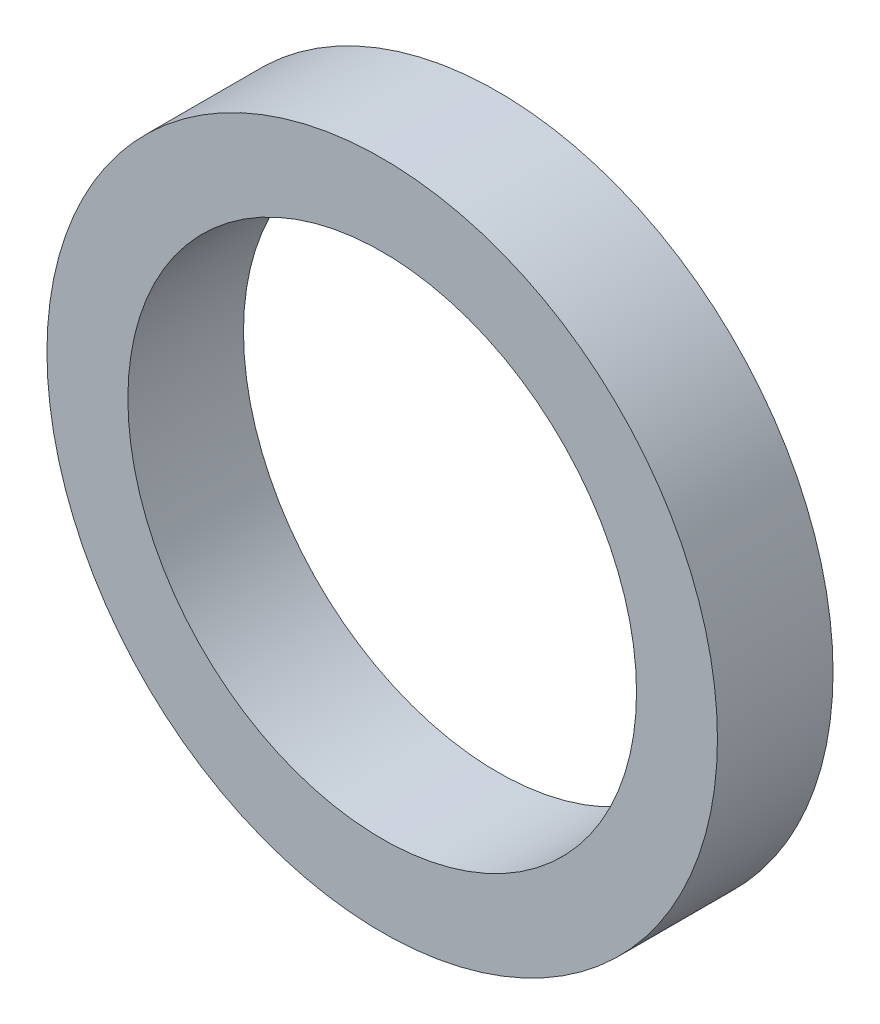
SolidWorks part; units mm, degrees
ref_plane "정면" through (0, 0, 0) normal (0, 0, 1) x (1, 0, 0)
ref_plane "윗면" through (0, 0, 0) normal (0, 1, 0) x (1, 0, 0)
ref_plane "우측면" through (0, 0, 0) normal (1, 0, 0) x (0, 0, -1)
sketch "스케치1" plane through (0, 0, 0) normal (0, 0, 1) x (1, 0, 0)
  circle A0 centre (0, 0) radius 72.5
  circle A1 centre (0, 0) radius 55
  dimension "D1" = 145
  dimension "D2" = 110
extrude "보스-돌출1" add sketch "스케치1" along normal blind 25
